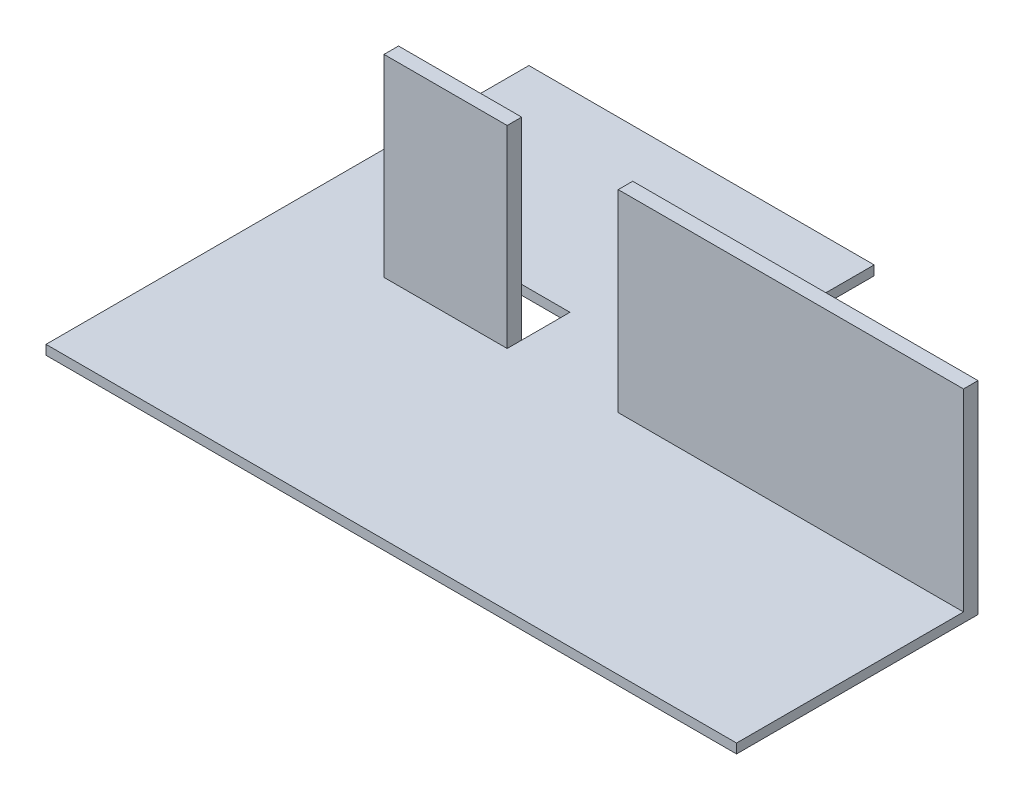
SolidWorks part; units mm, degrees
material "1023 Carbon Steel Sheet (SS)"
ref_plane "Front Plane" through (0, 0, 0) normal (0, 0, 1) x (1, 0, 0)
ref_plane "Top Plane" through (0, 0, 0) normal (0, 1, 0) x (1, 0, 0)
ref_plane "Right Plane" through (0, 0, 0) normal (1, 0, 0) x (0, 0, -1)
sketch "Sketch1" plane through (0, 0, 0) normal (0, 1, 0) x (1, 0, 0)
  line L0 (0, 0) -> (-18.161, 0) construction
  line L1 (-18.161, -12.7) -> (18.161, -12.7)
  line L2 (-18.161, -12.7) -> (-18.161, 12.7)
  line L3 (-18.161, 12.7) -> (0, 12.7)
  line L4 (18.161, -12.7) -> (18.161, 0)
  line L5 (-18.161, -12.7) -> (0, 0) construction
  line L6 (-18.161, 12.7) -> (18.161, -12.7) construction
  line L7 (-12.319, 0) -> (-5.842, 0)
  line L8 (-12.319, 0) -> (-12.319, 2.54)
  line L9 (18.161, 0) -> (0, 0)
  line L10 (0, 12.7) -> (0, 0)
  line L11 (-12.319, 2.54) -> (-5.842, 2.54)
  line L12 (-5.842, 0) -> (-5.842, 2.54)
  line L13 (-12.319, 0) -> (-5.842, 2.54) construction
  line L14 (-12.319, 2.54) -> (-5.842, 0) construction
  line L15 (-9.0805, 12.7) -> (-9.0805, 1.27) construction
  point P0 (0, 0)
  point P1 (-9.0805, 1.27)
  dimension "D1" = 36.322
  dimension "D2" = 12.7
  dimension "D3" = 5.842
  dimension "D4" = 2.54
  dimension "D5" = 5.842
extrude "Boss-Extrude1" add sketch "Sketch1" along normal blind 0.5
sketch "Sketch2" plane through (0, 0.5, 0) normal (0, 1, 0) x (1, 0, 0)
  line L0 (18.161, 0) -> (0, 0) construction
  line L1 (-5.842, 0) -> (-12.319, 0)
  line L2 (-5.842, 0) -> (-5.842, -0.762)
  line L3 (-5.842, -0.762) -> (-12.319, -0.762)
  line L4 (-12.319, 0) -> (-12.319, -0.762)
  line L5 (0, 0) -> (18.161, 0)
  line L6 (0, 0) -> (0, -0.762)
  line L7 (0, -0.762) -> (18.161, -0.762)
  line L8 (18.161, 0) -> (18.161, -0.762)
  dimension "D1" = 6.477
  dimension "D2" = 0.762
  dimension "D3" = 0.762
extrude "Boss-Extrude2" add sketch "Sketch2" along normal blind 10.16 contours L5 L8 L7 L6
